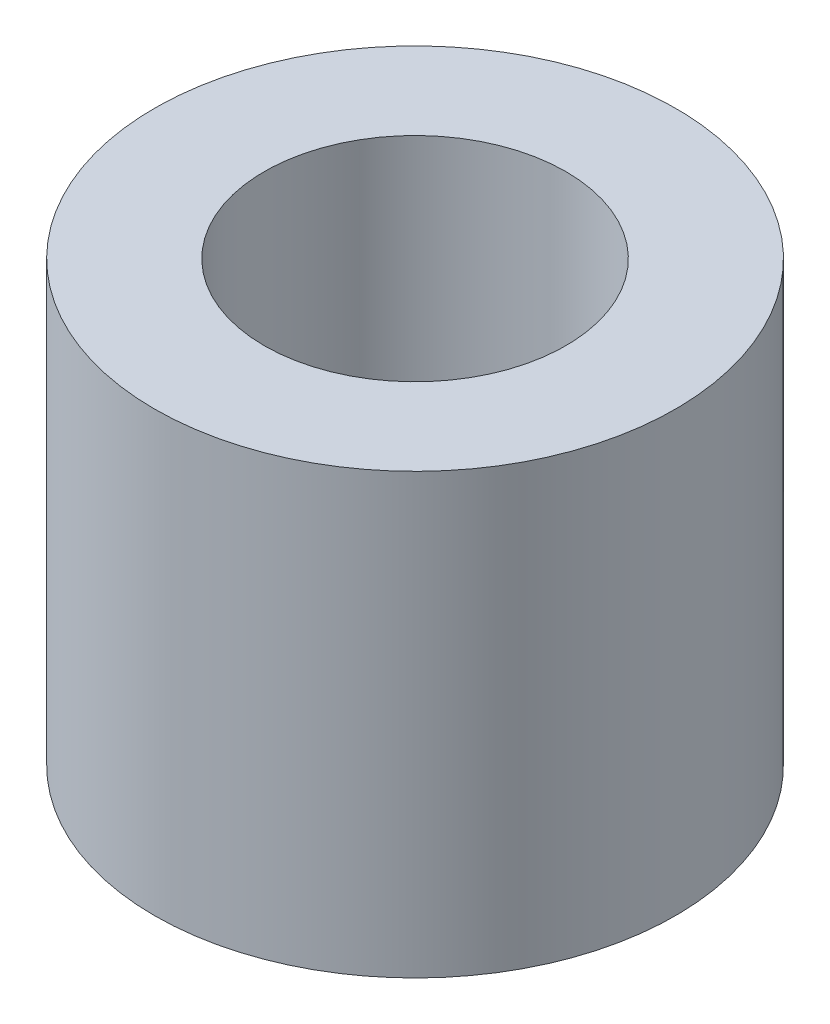
SolidWorks part; units mm, degrees
ref_plane "Alzado" through (0, 0, 0) normal (0, 0, 1) x (1, 0, 0)
ref_plane "Planta" through (0, 0, 0) normal (0, 1, 0) x (1, 0, 0)
ref_plane "Vista lateral" through (0, 0, 0) normal (1, 0, 0) x (0, 0, -1)
sketch "Croquis1" plane through (0, 0, 0) normal (0, 1, 0) x (1, 0, 0)
  circle A0 centre (0, 0) radius 9.5
  dimension "D1" = 19
extrude "Saliente-Extruir1" add sketch "Croquis1" along normal blind 16
sketch "Croquis2" plane through (0, 16, 0) normal (0, 1, 0) x (1, 0, 0)
  circle A0 centre (0, 0) radius 5.5
  dimension "D1" = 11
extrude "Cortar-Extruir1" cut sketch "Croquis2" against normal up to next
